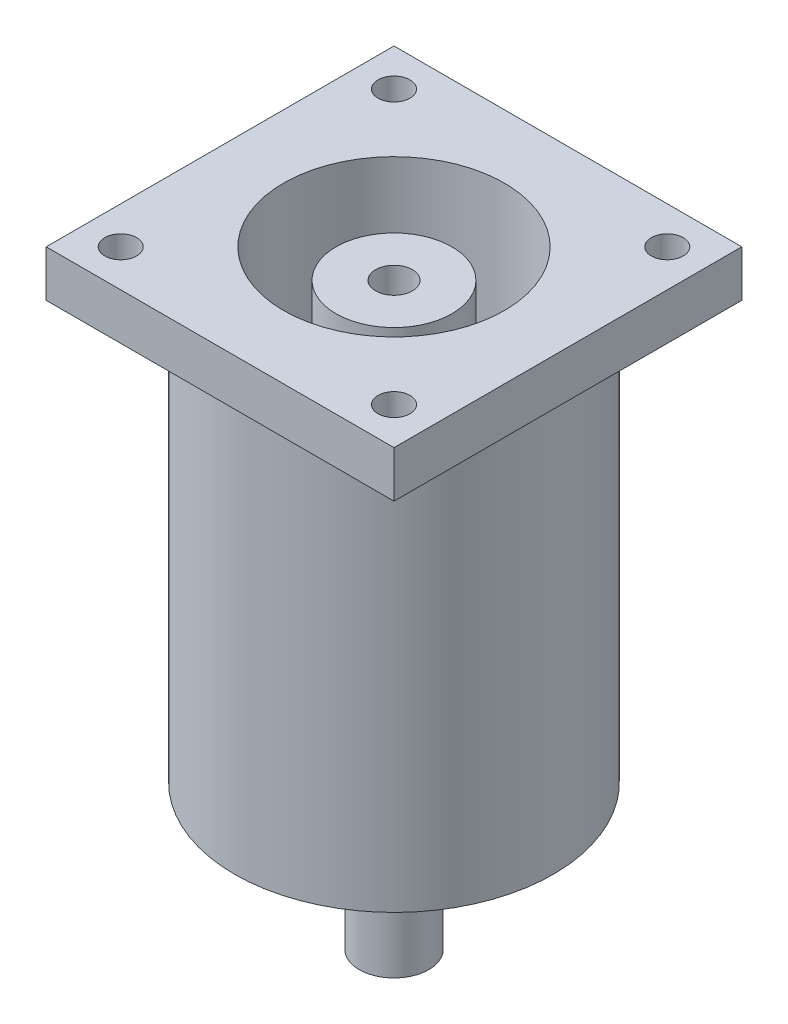
SolidWorks part; units mm, degrees
ref_plane "Front Plane" through (0, 0, 0) normal (0, 0, 1) x (1, 0, 0)
ref_plane "Top Plane" through (0, 0, 0) normal (0, 1, 0) x (1, 0, 0)
ref_plane "Right Plane" through (0, 0, 0) normal (1, 0, 0) x (0, 0, -1)
sketch "Sketch1" plane through (0, 0, 0) normal (0, 1, 0) x (1, 0, 0)
  circle A0 centre (0, 0) radius 27.5
  dimension "D1" = 55
extrude "Boss-Extrude1" add sketch "Sketch1" along normal blind 72
sketch "Sketch2" plane through (0, 0, 0) normal (0, -1, 0) x (1, 0, 0)
  circle A0 centre (0, 0) radius 16
  dimension "D1" = 32
extrude "Boss-Extrude2" add sketch "Sketch2" along normal blind 2.5
sketch "Sketch3" plane through (0, 72, 0) normal (0, 1, 0) x (1, 0, 0)
  line L1 (-30, 30) -> (30, 30)
  line L2 (-30, 30) -> (-30, -30)
  line L3 (-30, -30) -> (30, -30)
  line L4 (30, 30) -> (30, -30)
  line L5 (-30, 30) -> (30, -30) construction
  line L6 (-30, -30) -> (30, 30) construction
  point P0 (0, 0)
  dimension "D1" = 60
  dimension "D2" = 60
extrude "Boss-Extrude3" add sketch "Sketch3" along normal blind 8
sketch "Sketch4" plane through (0, -2.5, 0) normal (0, -1, 0) x (-1, 0, 0)
  circle A0 centre (0, 0) radius 6
  dimension "D1" = 12
extrude "Boss-Extrude4" add sketch "Sketch4" along normal blind 22.5
sketch "Sketch5" plane through (0, 0, 0) normal (0, -1, 0) x (1, 0, 0)
  line L0 (0, 0) -> (30, 30)
  circle A0 centre (0, 0) radius 20
  circle A1 centre (14.1421, 14.1421) radius 2
  circle A2 centre (14.1421, -14.1421) radius 2
  circle A3 centre (-14.1421, -14.1421) radius 2
  circle A4 centre (-14.1421, 14.1421) radius 2
  point P15 (0, 0)
  dimension "D1" = 40
  dimension "D2" = 4
  dimension "D3" = 4
extrude "Cut-Extrude1" cut sketch "Sketch5" against normal blind 16 contours A1 | A4 | A3 | A2
sketch "Sketch6" plane through (0, 80, 0) normal (0, 1, 0) x (1, 0, 0)
  circle A0 centre (0, 0) radius 19.05
  dimension "D1" = 38.1
extrude "Cut-Extrude2" cut sketch "Sketch6" against normal blind 25
sketch "Sketch7" plane through (0, 55, 0) normal (0, 1, 0) x (1, 0, 0)
  circle A0 centre (0, 0) radius 10
  circle A1 centre (0, 0) radius 3.175
  dimension "D1" = 6.35
  dimension "D2" = 20
extrude "Boss-Extrude5" add sketch "Sketch7" along normal blind 20
sketch "Sketch8" plane through (0, 80, 0) normal (0, 1, 0) x (1, 0, 0)
  line L0 (-30, 30) -> (0, 0)
  line L1 (23.5714, -23.5714) -> (-23.5714, 23.5714)
  line L2 (-23.5714, -23.5714) -> (23.5714, 23.5714)
  circle A0 centre (-23.5714, 23.5714) radius 2.75
  circle A1 centre (0, 0) radius 33.335
  circle A2 centre (23.5714, 23.5714) radius 2.75
  circle A3 centre (23.5714, -23.5714) radius 2.75
  circle A4 centre (-23.5714, -23.5714) radius 2.75
  point P6 (0, 0)
  point P7 (0, 0)
  point P14 (0.0223, 0.0224)
  point P17 (0, 0)
  point P20 (0, 0)
  dimension "D1" = 5.5
  dimension "D2" = 90
  dimension "D5" = 66.67
  dimension "D3" = 5.5
  dimension "D4" = 5.5
  dimension "D6" = 5.5
extrude "Cut-Extrude3" cut sketch "Sketch8" against normal blind 10 contours A3 | A4 | A0 | A2
